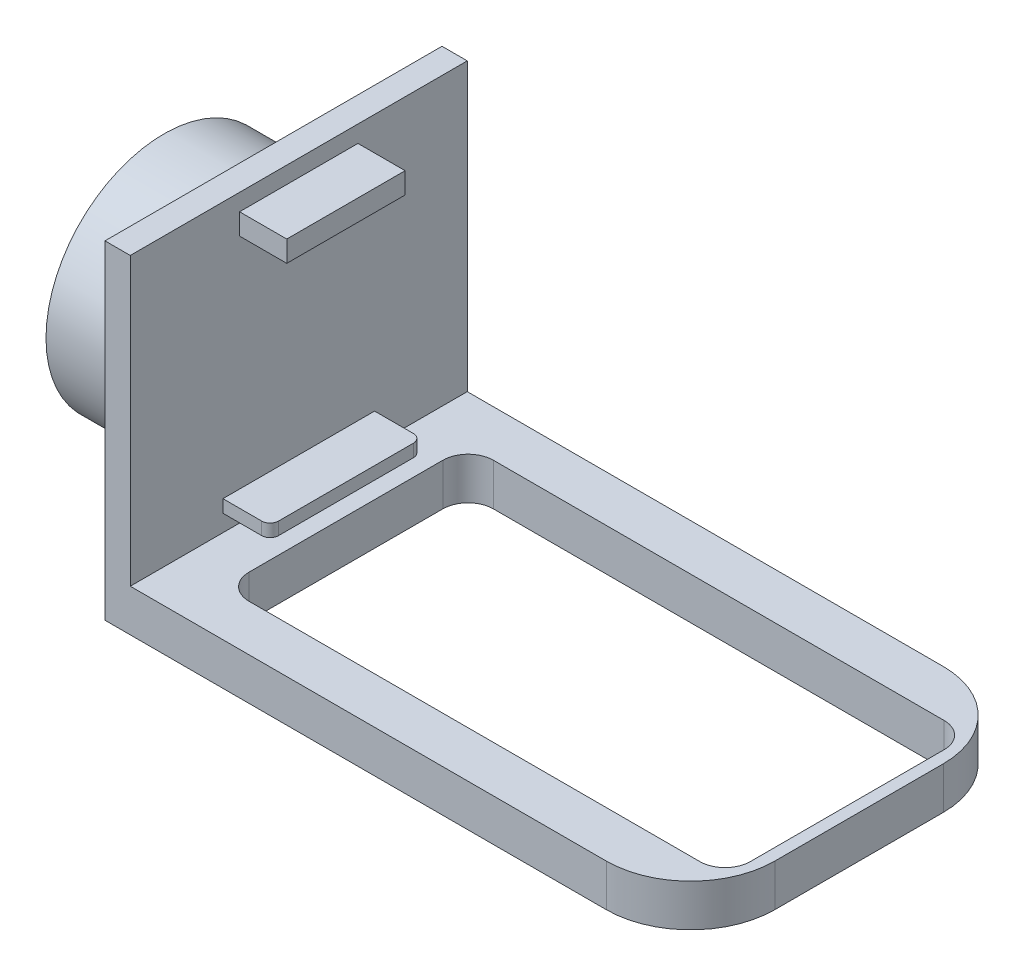
SolidWorks part; units mm, degrees
ref_plane "Front Plane" through (0, 0, 0) normal (0, 0, 1) x (1, 0, 0)
ref_plane "Top Plane" through (0, 0, 0) normal (0, 1, 0) x (1, 0, 0)
ref_plane "Right Plane" through (0, 0, 0) normal (1, 0, 0) x (0, 0, -1)
sketch "Sketch2" plane through (0, 0, 0) normal (0, 1, 0) x (1, 0, 0)
  line L0 (-27.65, 11.5) -> (-27.65, -11.5)
  line L7 (-33.25, -20) -> (33.25, -20)
  line L8 (-33.25, -20) -> (-33.25, 20)
  line L9 (-33.25, 20) -> (33.25, 20)
  line L10 (33.25, -20) -> (33.25, 20)
  line L11 (-24.65, 14.5) -> (28.85, 14.5)
  line L12 (31.85, 11.5) -> (31.85, -11.5)
  line L13 (28.85, -14.5) -> (-24.65, -14.5)
  arc A4 (31.85, -11.5) -> (28.85, -14.5) centre (28.85, -11.5) cw
  arc A5 (28.85, 14.5) -> (31.85, 11.5) centre (28.85, 11.5) cw
  arc A6 (-27.65, 11.5) -> (-24.65, 14.5) centre (-24.65, 11.5) cw
  arc A7 (-27.65, -11.5) -> (-24.65, -14.5) centre (-24.65, -11.5) ccw
  point P0 (0, 0)
  point P7 (0, 0)
  dimension "D1" = 3
extrude "Boss-Extrude1" add sketch "Sketch2" along normal blind 5
sketch "Sketch5" plane through (-33.25, 0, 0) normal (-1, 0, 0) x (0, 0, 1)
  line L1 (20, 0) -> (-20, 0)
  line L2 (20, 0) -> (20, 39)
  line L3 (20, 39) -> (-20, 39)
  line L4 (-20, 0) -> (-20, 39)
  dimension "D1" = 39
extrude "Boss-Extrude3" add sketch "Sketch5" along normal blind 3
sketch "Sketch11" plane through (-33.25, 0, 0) normal (1, 0, 0) x (0, 0, -1)
  line L6 (0, 37) -> (-7.025, 37)
  line L7 (0, 37) -> (7.025, 37)
  line L11 (-7.025, 37) -> (-7.025, 34.5)
  line L12 (-7.025, 34.5) -> (7.025, 34.5)
  line L13 (7.025, 34.5) -> (7.025, 37)
  line L14 (0, 7) -> (-9, 7)
  line L15 (0, 7) -> (9, 7)
  line L16 (9, 7) -> (9, 8.5)
  line L17 (9, 8.5) -> (-9, 8.5)
  line L18 (-9, 8.5) -> (-9, 7)
extrude "Boss-Extrude4" add sketch "Sketch11" along normal blind 5.6
fillet "Fillet4" radius 1 2 edges at (-27.65, 7.75, 9) (-27.65, 7.75, -9)
sketch "Sketch12" plane through (-36.25, 0, 0) normal (-1, 0, 0) x (0, 0, 1)
  circle A0 centre (0, 19.5) radius 4
extrude "Boss-Extrude5" add sketch "Sketch12" along normal blind 3
fillet "Fillet6" radius 10 2 edges at (33.25, 2.5, 20) (33.25, 2.5, -20)
sketch "Sketch13" plane through (-39.25, 0, 0) normal (-1, 0, 0) x (0, 0, 1)
  circle A0 centre (0, 19.5) radius 14
extrude "Boss-Extrude6" add sketch "Sketch13" along normal blind 10
sketch "Sketch14" plane through (-49.25, 0, 0) normal (-1, 0, 0) x (0, 0, 1)
  circle A0 centre (0, 19.5) radius 5
extrude "Cut-Extrude1" cut sketch "Sketch14" against normal blind 5
sketch "Sketch15" plane through (-44.25, 0, 0) normal (-1, 0, 0) x (0, 0, 1)
  circle A0 centre (0, 19.5) radius 2.25
extrude "Cut-Extrude2" cut sketch "Sketch15" against normal blind 3
